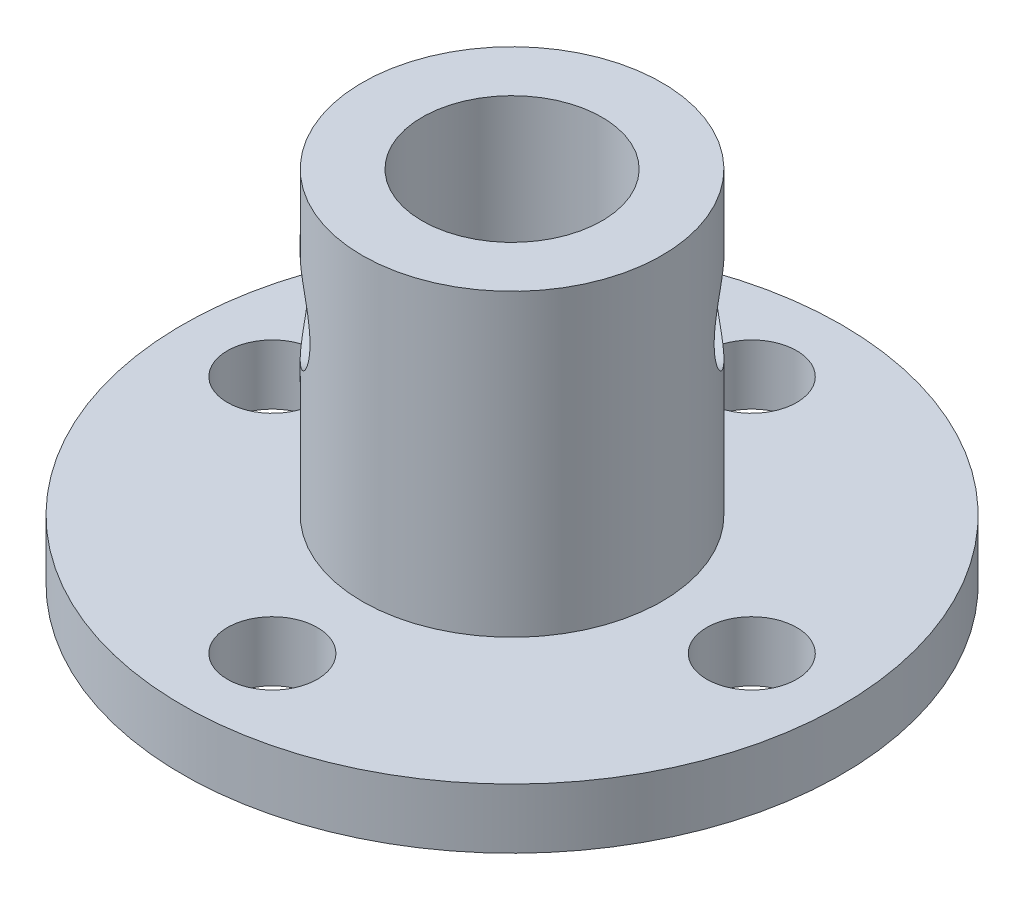
SolidWorks part; units mm, degrees
material "AISI 1045 钢，冷拔"
ref_plane "前视基准面" through (0, 0, 0) normal (0, 0, 1) x (1, 0, 0)
ref_plane "上视基准面" through (0, 0, 0) normal (0, 1, 0) x (1, 0, 0)
ref_plane "右视基准面" through (0, 0, 0) normal (1, 0, 0) x (0, 0, -1)
sketch "草图1" plane through (0, 0, 0) normal (0, 1, 0) x (1, 0, 0)
  circle A0 centre (0, 0) radius 11
  circle A1 centre (0, 0) radius 3
  dimension "D1" = 22
  dimension "6" = 6
extrude "凸台-拉伸1" add sketch "草图1" along normal blind 2
sketch "草图2" plane through (0, 2, 0) normal (0, 1, 0) x (1, 0, 0)
  circle A1 centre (0, 0) radius 5
  circle A2 centre (0, 0) radius 3 construction
  circle A3 centre (0, 0) radius 3
  dimension "D1" = 10
extrude "凸台-拉伸2" add sketch "草图2" along normal blind 10
sketch "草图3" plane through (0, 2, 0) normal (0, 1, 0) x (1, 0, 0)
  circle A0 centre (-8, 0) radius 1.5
  circle A1 centre (0, 0) radius 3 construction
  circle A2 centre (0, 8) radius 1.5
  circle A3 centre (8, 0) radius 1.5
  circle A4 centre (0, -8) radius 1.5
  point P14 (0, 0)
  dimension "D1" = 8
  dimension "D2" = 3
  dimension "D3" = 8
  dimension "D5" = 8
  dimension "D6" = 8
  dimension "D4" = 4
hole_wizard "大小mm Press 暗销孔1" positions "草图4" profile "草图5" hole size "Ø3.0" standard "GB" end condition up to next
sketch "草图4" plane through (0, 2, 0) normal (0, 1, 0) x (1, 0, 0)
  point P0 (-8, 0)
  point P3 (0, 8)
  point P6 (8, 0)
  point P9 (0, -8)
sketch "草图5" plane through (-8, 2, 0) normal (1, 0, 0) x (0, 0, 1)
  line L0 (0, 0) -> (0, 2)
  line L1 (0, 2) -> (1.5, 2)
  line L2 (1.5, 2) -> (1.5, 0)
  line L5 (1.5, 0) -> (0, 0)
  line L11 (0, -6.35) -> (0, 107.95) construction
  dimension "通孔孔直径" = 3
  dimension "通孔孔深度" = 2
sketch "草图7" plane through (0, 0, 0) normal (1, 0, 0) x (0, 0, -1)
  line L1 (0, 0) -> (0, 21.6239)
  dimension "D1" = 21.6239
ref_plane "基准面1" through (0, 0, 0) normal (0.7071, 0, -0.7071) x (0, 1, 0)
sketch "草图6" plane through (0, 0, 0) normal (0.7071, 0, -0.7071) x (-0.7071, 0, -0.7071)
  line L1 (1.5, 8) -> (-1.5, 8)
  line L2 (1.5, 8) -> (1.5, 18.6931)
  line L3 (1.5, 18.6931) -> (-1.5, 18.6931)
  line L4 (-1.5, 8) -> (-1.5, 18.6931)
  circle A0 centre (0, 8) radius 1.5
  dimension "D1" = 8
  dimension "D2" = 0
  dimension "D3" = 3
  dimension "D4" = 10.6931
  dimension "D5" = 3
extrude "切除-拉伸1" cut sketch "草图6" against normal through all both and the other way through all contours L1 A0 | L1 A0
